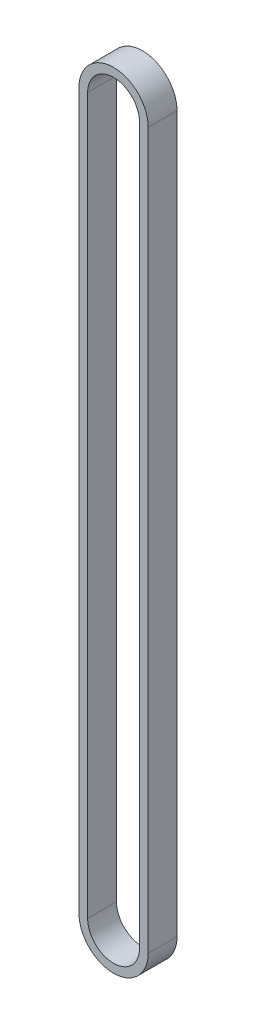
SolidWorks part; units mm, degrees
ref_plane "前视基准面" through (0, 0, 0) normal (0, 0, 1) x (1, 0, 0)
ref_plane "上视基准面" through (0, 0, 0) normal (0, 1, 0) x (1, 0, 0)
ref_plane "右视基准面" through (0, 0, 0) normal (1, 0, 0) x (0, 0, -1)
sketch "草图1" plane through (0, 0, 0) normal (0, 0, 1) x (1, 0, 0)
  line L0 (0, 0) -> (0, 248)
  line L1 (-12, 248) -> (-12, 0)
  line L2 (12, 0) -> (12, 248)
  line L3 (-9, 248) -> (-9, 0)
  line L4 (9, 0) -> (9, 248)
  circle A0 centre (0, 248) radius 12
  circle A1 centre (0, 0) radius 12
  circle A2 centre (0, 0) radius 9
  circle A3 centre (0, 248) radius 9
  dimension "D2" = 18
  dimension "D3" = 24
  dimension "D4" = 18
  dimension "D5" = 24
  dimension "D1" = 248
extrude "凸台-拉伸1" add sketch "草图1" along normal blind 10 contours A3 L4 A0 L3 | A1 L3 A0 L1 | A1 L2 A0 L4 | A2 L3 A1 L4
